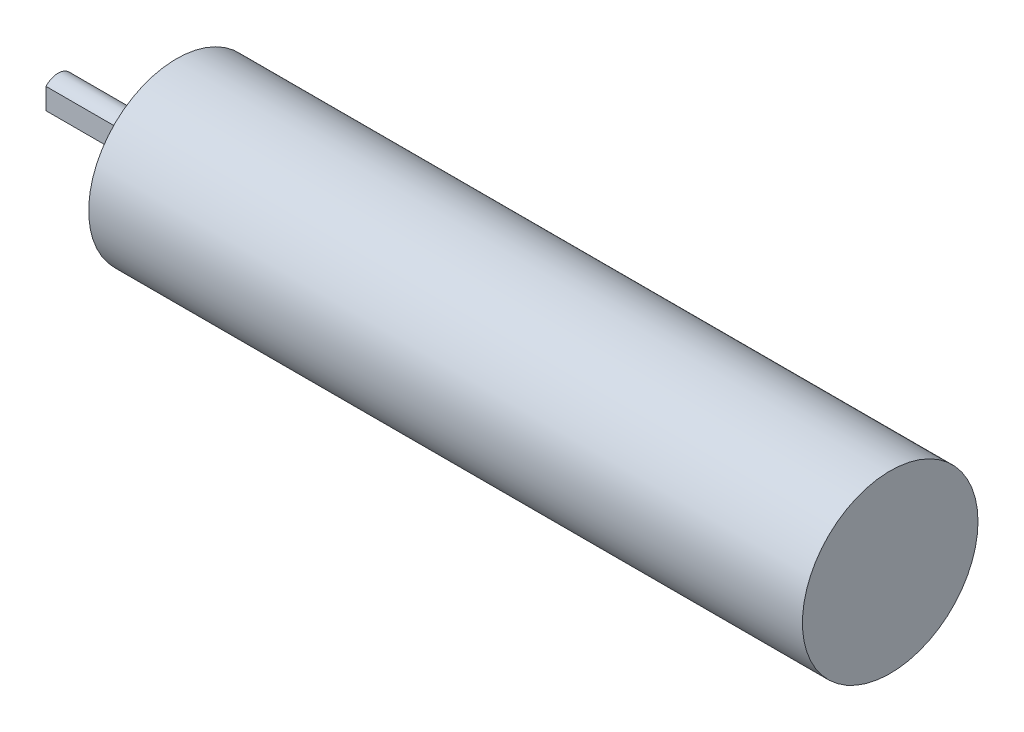
SolidWorks part; units mm, degrees
ref_plane "Front Plane" through (0, 0, 0) normal (0, 0, 1) x (1, 0, 0)
ref_plane "Top Plane" through (0, 0, 0) normal (0, 1, 0) x (1, 0, 0)
ref_plane "Right Plane" through (0, 0, 0) normal (1, 0, 0) x (0, 0, -1)
sketch "Sketch1" plane through (0, 0, 0) normal (0, 0, 1) x (1, 0, 0)
  line L0 (0, 11) -> (0, 0)
  line L1 (0, 0) -> (52.6, 0)
  line L2 (52.6, 0) -> (52.6, 11)
  line L3 (52.6, 11) -> (0, 11)
  line L4 (0, 0) -> (52.6, 0) construction
revolve "Revolve1" add sketch "Sketch1" angle 360 about L4
sketch "Sketch2" plane through (0, 0, 0) normal (-1, 0, 0) x (0, 0, 1)
  circle A0 centre (0, 0) radius 5
extrude "Boss-Extrude1" add sketch "Sketch2" along normal blind 1.35
sketch "Sketch3" plane through (-1.35, 0, 0) normal (-1, 0, 0) x (0, 0, 1)
  circle A0 centre (0, 0) radius 3.5
extrude "Boss-Extrude2" add sketch "Sketch3" along normal blind 1.8
sketch "Sketch4" plane through (-3.15, 0, 0) normal (-1, 0, 0) x (0, 0, 1)
  circle A0 centre (0, 0) radius 2
extrude "Boss-Extrude3" add sketch "Sketch4" along normal blind 11.7
ref_plane "Plane1" through (-3.675, 0, 3.675) normal (0.7071, 0, -0.7071) x (0, 1, 0)
sketch "Sketch6" plane through (-14.85, 0, 0) normal (-1, 0, 0) x (0, 0, 1)
  line L0 (1.5, 1.3229) -> (1.5, -1.3229)
  arc A0 (1.5, -1.3229) -> (1.5, 1.3229) centre (0, 0) ccw
extrude "Cut-Extrude1" cut sketch "Sketch6" against normal up to surface up to plane "Plane1"
hole_wizard "Hole1" positions "Sketch8" profile "Sketch7" legacy
sketch "Sketch8" plane through (0, 0, 0) normal (-1, 0, 0) x (0, 0, 1)
  point P0 (7, 0)
sketch "Sketch7" plane through (0, 0, 7) normal (0, 1, 0) x (0, 0, 1)
  line L0 (0, 0) -> (0, 6.5)
  line L1 (0, 6.5) -> (0.975, 6.5)
  line L2 (0.975, 6.5) -> (0.975, 0)
  line L3 (0.975, 0) -> (0, 0)
  line L4 (0, 110) -> (0, -10) construction
  dimension "Diameter" = 1.95
  dimension "Depth" = 6.5
hole_wizard "Hole2" positions "Sketch10" profile "Sketch9" legacy
sketch "Sketch10" plane through (0, 0, 0) normal (-1, 0, 0) x (0, 0, 1)
  point P0 (-3.5, -6.0622)
sketch "Sketch9" plane through (0, -6.0622, -3.5) normal (0, 1, 0) x (0, 0, 1)
  line L0 (0, 0) -> (0, 6.5)
  line L1 (0, 6.5) -> (0.975, 6.5)
  line L2 (0.975, 6.5) -> (0.975, 0)
  line L3 (0.975, 0) -> (0, 0)
  line L4 (0, 110) -> (0, -10) construction
  dimension "Diameter" = 1.95
  dimension "Depth" = 6.5
hole_wizard "Hole3" positions "Sketch12" profile "Sketch11" legacy
sketch "Sketch12" plane through (0, 0, 0) normal (-1, 0, 0) x (0, 0, 1)
  point P0 (-3.5, 6.0622)
sketch "Sketch11" plane through (0, 6.0622, -3.5) normal (0, 1, 0) x (0, 0, 1)
  line L0 (0, 0) -> (0, 6.5)
  line L1 (0, 6.5) -> (0.975, 6.5)
  line L2 (0.975, 6.5) -> (0.975, 0)
  line L3 (0.975, 0) -> (0, 0)
  line L4 (0, 110) -> (0, -10) construction
  dimension "Diameter" = 1.95
  dimension "Depth" = 6.5
hole_wizard "Hole4" positions "Sketch14" profile "Sketch13" legacy
sketch "Sketch14" plane through (52.6, 0, 0) normal (1, 0, 0) x (0, 0, -1)
  point P0 (0, 0)
sketch "Sketch13" plane through (52.6, 0, 0) normal (0, 1, 0) x (0, 0, -1)
  line L0 (0, 0) -> (0, 6.4)
  line L1 (0, 6.4) -> (3.5, 6.4)
  line L2 (3.5, 6.4) -> (3.5, 0)
  line L3 (3.5, 0) -> (0, 0)
  line L4 (0, 110) -> (0, -10) construction
  dimension "Diameter" = 7
  dimension "Depth" = 6.4
hole_wizard "Hole5" positions "Sketch16" profile "Sketch15" legacy
sketch "Sketch16" plane through (52.6, 0, 0) normal (1, 0, 0) x (0, 0, -1)
  point P0 (-8.5, 0)
sketch "Sketch15" plane through (52.6, 0, 8.5) normal (0, 1, 0) x (0, 0, -1)
  line L0 (0, 0) -> (0, 3)
  line L1 (0, 3) -> (1.05, 3)
  line L2 (1.05, 3) -> (1.05, 0)
  line L3 (1.05, 0) -> (0, 0)
  line L4 (0, 110) -> (0, -10) construction
  dimension "Diameter" = 2.1
  dimension "Depth" = 3
hole_wizard "Hole6" positions "Sketch18" profile "Sketch17" legacy
sketch "Sketch18" plane through (52.6, 0, 0) normal (1, 0, 0) x (0, 0, -1)
  point P0 (4.25, -7.3612)
sketch "Sketch17" plane through (52.6, -7.3612, -4.25) normal (0, 1, 0) x (0, 0, -1)
  line L0 (0, 0) -> (0, 3)
  line L1 (0, 3) -> (1.05, 3)
  line L2 (1.05, 3) -> (1.05, 0)
  line L3 (1.05, 0) -> (0, 0)
  line L4 (0, 110) -> (0, -10) construction
  dimension "Diameter" = 2.1
  dimension "Depth" = 3
hole_wizard "Hole7" positions "Sketch20" profile "Sketch19" legacy
sketch "Sketch20" plane through (52.6, 0, 0) normal (1, 0, 0) x (0, 0, -1)
  point P0 (4.25, 7.3612)
sketch "Sketch19" plane through (52.6, 7.3612, -4.25) normal (0, 1, 0) x (0, 0, -1)
  line L0 (0, 0) -> (0, 3)
  line L1 (0, 3) -> (1.05, 3)
  line L2 (1.05, 3) -> (1.05, 0)
  line L3 (1.05, 0) -> (0, 0)
  line L4 (0, 110) -> (0, -10) construction
  dimension "Diameter" = 2.1
  dimension "Depth" = 3
ref_plane "Plane2" through (52.6, 0, 0) normal (1, 0, 0) x (0, 0, -1)
sketch "Sketch25" plane through (52.6, 0, 0) normal (1, 0, 0) x (0, 0, -1)
  circle A0 centre (0, 0) radius 11
extrude "Boss-Extrude4" add sketch "Sketch25" along normal blind 36.83
